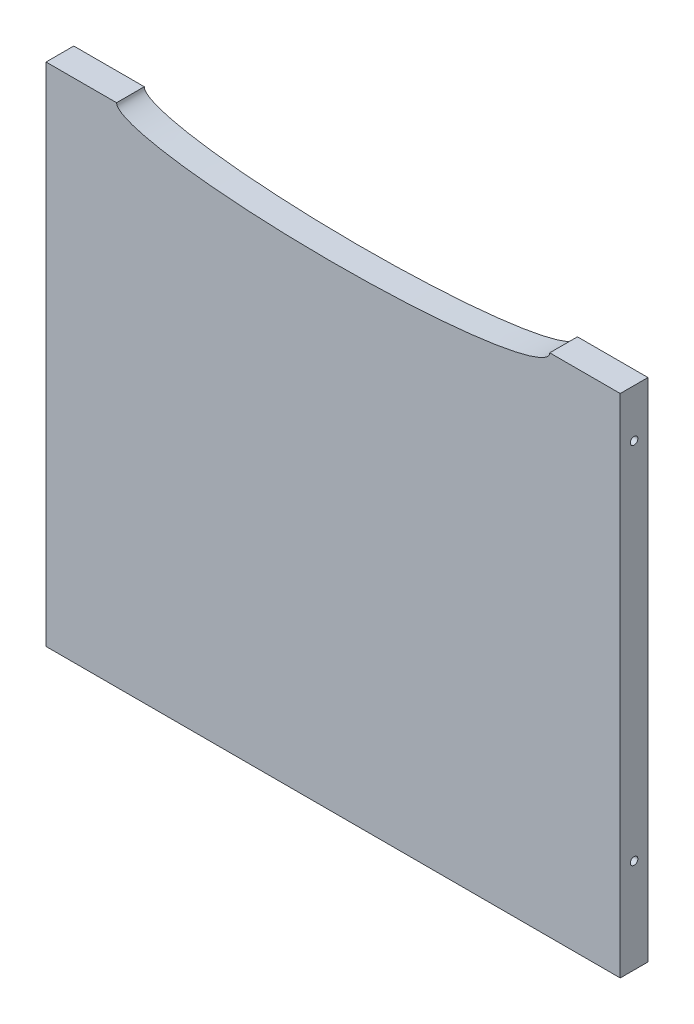
SolidWorks part; units mm, degrees
material "ParticleBoard"
ref_plane "Front Plane" through (0, 0, 0) normal (0, 0, 1) x (1, 0, 0)
ref_plane "Top Plane" through (0, 0, 0) normal (0, 1, 0) x (1, 0, 0)
ref_plane "Right Plane" through (0, 0, 0) normal (1, 0, 0) x (0, 0, -1)
sketch "PanelSketch" plane through (0, 0, 0) normal (0, 0, 1) x (1, 0, 0)
  line L1 (-180.975, -159.5438) -> (180.975, -159.5438)
  line L2 (-180.975, -159.5438) -> (-180.975, 159.5437)
  line L3 (-180.975, 159.5437) -> (180.975, 159.5437)
  line L4 (180.975, -159.5438) -> (180.975, 159.5437)
  line L5 (-180.975, -159.5438) -> (180.975, 159.5437) construction
  line L6 (-180.975, 159.5437) -> (180.975, -159.5438) construction
  ellipse E0 centre (0, 159.5437) end of major axis (136.525, 159.5437) minor radius 19.05
  point P0 (0, 0)
  dimension "D1" = 361.95
  dimension "D2" = 319.0875
  dimension "D3" = 44.45
  dimension "D4" = 19.05
extrude "Boss-Extrude1" add sketch "PanelSketch" along normal blind 17.4625 contours E0 L3 L2 L1 L4
sketch "RightScrewHoles" plane through (180.975, 0, 0) normal (1, 0, 0) x (0, 0, -1)
  line L0 (-17.4625, 159.5437) -> (0, 159.5437) construction
  line L1 (-17.4625, -159.5438) -> (0, -159.5438) construction
  circle A0 centre (-8.7312, 129.3812) radius 2.3812
  circle A1 centre (-8.7312, -100.0125) radius 2.3812
  dimension "D3" = 4.7625
  dimension "D4" = 4.7625
  dimension "D1" = 30.1625
  dimension "D2" = 59.5312
extrude "Cut-Extrude1" cut sketch "RightScrewHoles" against normal blind 50.8
sketch "LeftScrewHoles" plane through (-180.975, 0, 0) normal (-1, 0, 0) x (0, 0, 1)
  line L0 (17.4625, -159.5438) -> (0, -159.5438) construction
  line L1 (17.4625, 159.5437) -> (0, 159.5437) construction
  circle A0 centre (8.7312, 129.3812) radius 2.3812
  circle A1 centre (8.7312, -100.0125) radius 2.3812
  dimension "D2" = 4.7625
  dimension "D4" = 4.7625
  dimension "D1" = 59.5312
  dimension "D3" = 30.1625
extrude "Cut-Extrude2" cut sketch "LeftScrewHoles" against normal blind 50.8
sketch "BottomScrewHoles" plane through (0, -159.5438, 0) normal (0, -1, 0) x (1, 0, 0)
  line L0 (-180.975, 17.4625) -> (-180.975, 0) construction
  line L1 (180.975, 17.4625) -> (180.975, 0) construction
  circle A0 centre (-111.125, 8.7312) radius 2.3813
  circle A1 centre (111.125, 8.7312) radius 2.3813
  dimension "D2" = 4.7625
  dimension "D3" = 4.7625
  dimension "D1" = 69.85
  dimension "D4" = 69.85
extrude "Cut-Extrude3" cut sketch "BottomScrewHoles" against normal blind 50.8
